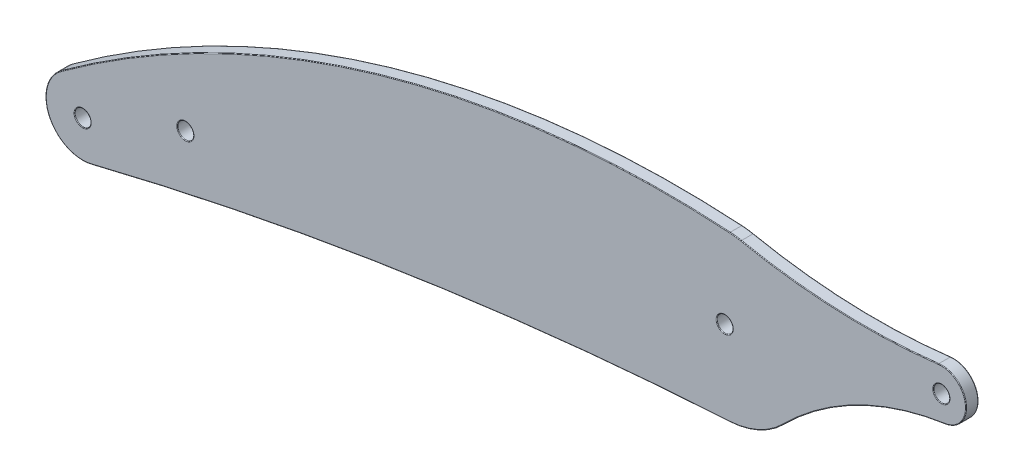
SolidWorks part; units mm, degrees
ref_plane "Front Plane" through (0, 0, 0) normal (0, 0, 1) x (1, 0, 0)
ref_plane "Top Plane" through (0, 0, 0) normal (0, 1, 0) x (1, 0, 0)
ref_plane "Right Plane" through (0, 0, 0) normal (1, 0, 0) x (0, 0, -1)
sketch "Sketch1" plane through (0, 0, 0) normal (0, 0, 1) x (1, 0, 0)
  line L0 (-176.6205, 170.9379) -> (32.3034, 217.2715) construction
  line L1 (-176.6205, 170.9379) -> (32.3034, 217.2715) construction
  circle A0 centre (-176.6205, 170.9379) radius 9 construction
  circle A1 centre (32.3034, 217.2715) radius 6 construction
  circle A2 centre (-20.4157, 205.5799) radius 10 construction
  circle A3 centre (-20.4157, 205.5799) radius 20 construction
  arc A4 (-174.4621, 162.2006) -> (-19.2708, 185.6127) centre (29.3879, -662.9934) cw
  arc A5 (-181.9141, 178.2165) -> (-19.1589, 225.5403) centre (-34.8685, -23.9656) cw
  arc A8 (-181.9141, 178.2165) -> (-174.4621, 162.2006) centre (-176.6205, 170.9379) ccw
  arc A12 (-176.6205, 170.9379) -> (-60.5313, 208.4028) centre (123.3301, -559.9038) cw construction
  arc A13 (-6.2424, 191.4689) -> (33.1766, 211.3354) centre (43.364, 142.0807) cw
  arc A14 (-16.4154, 225.1757) -> (31.5835, 223.2282) centre (13.5868, 372.1447) ccw
  arc A15 (-6.2424, 191.4689) -> (-19.2708, 185.6127) centre (-20.4157, 205.5799) cw
  arc A16 (-16.4154, 225.1757) -> (-19.1589, 225.5403) centre (-20.4157, 205.5799) ccw
  arc A17 (31.5835, 223.2282) -> (33.1766, 211.3354) centre (32.3034, 217.2715) cw
  point P2 (-20.4157, 205.5799)
  point P26 (-151.6205, 180.7055)
  point P27 (-52.1657, -1330.1643)
  dimension "D1" = 18
  dimension "D2" = 40
  dimension "D3" = 20
  dimension "D4" = 12
  dimension "D7" = 70
  dimension "D8" = 150
  dimension "D9" = 790
  dimension "D10" = 25
extrude "Boss-Extrude1" add sketch "Sketch1" against normal blind 3
hole_wizard "M3.5 Clearance Hole1" positions "Sketch3" profile "Sketch4" hole size "M3.5" standard "ISO"
sketch "Sketch3" plane through (0, 0, 0) normal (0, 0, 1) x (1, 0, 0)
  point P0 (32.3034, 217.2715)
  point P3 (-20.4157, 205.5799)
  point P6 (-52.1657, -1330.1643)
  point P9 (-151.6205, 180.7055)
  point P12 (-176.6205, 170.9379)
sketch "Sketch4" plane through (32.3034, 217.2715, 0) normal (1, 0, 0) x (0, -1, 0)
  line L0 (0, 0) -> (0, 11.1717)
  line L1 (0, 11.1717) -> (1.95, 10)
  line L2 (1.95, 10) -> (1.95, 0)
  line L5 (1.95, 0) -> (0, 0)
  line L10 (0, 11.1717) -> (-1.95, 10) construction
  line L11 (0, -6.35) -> (0, 107.95) construction
  dimension "Hole Dia." = 3.9
  dimension "Hole Depth" = 10
  dimension "Drill Angle" = 118
fillet "Fillet1" radius 0.15 24 edges at (-104.6695, 216.0924, 0) (-97.4079, 177.4962, 0) (-184.7804, 167.1412, 0) (-174.6705, 170.9379, 0) (-149.6705, 180.7055, 0) (-18.4657, 205.5799, 0) (34.2534, 217.2715, 0) (-97.4079, 177.4962, -3) (-104.6695, 216.0924, -3) (-184.7804, 167.1412, -3) (-174.6705, 170.9379, -3) (-149.6705, 180.7055, -3) (-18.4657, 205.5799, -3) (34.2534, 217.2715, -3) (-17.7809, 225.4056, 0) (7.5056, 222.268, 0) (38.2503, 218.0681, 0) (11.8601, 204.5907, 0) (-12.216, 187.338, 0) (-12.216, 187.338, -3) (11.8601, 204.5907, -3) (38.2503, 218.0681, -3) (7.5056, 222.268, -3) (-17.7809, 225.4056, -3)
